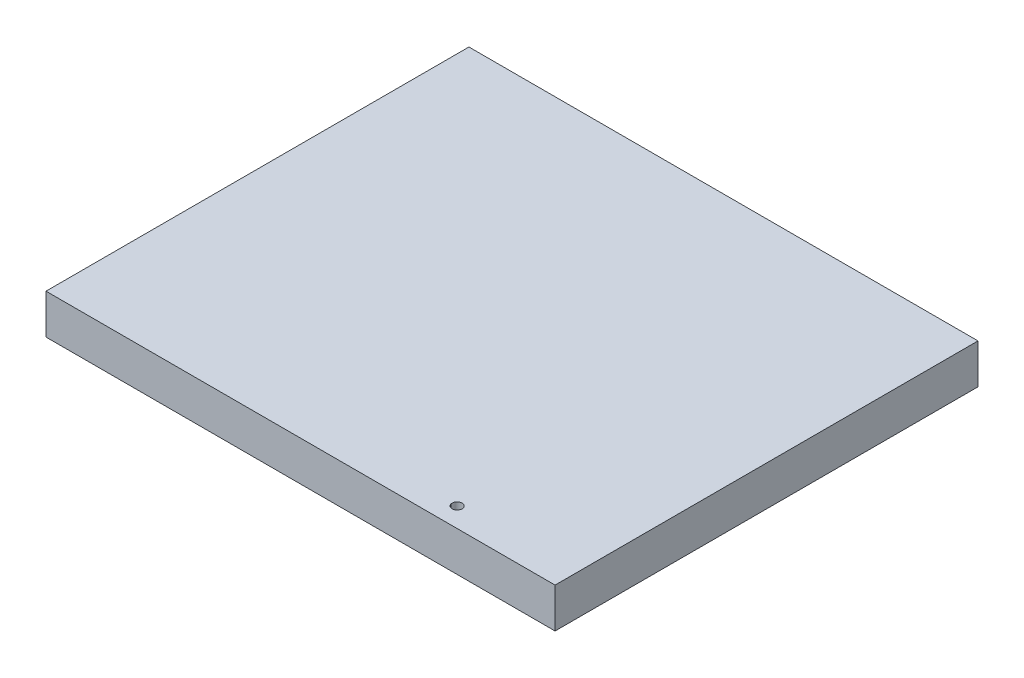
SolidWorks part; units mm, degrees
ref_plane "Front Plane" through (0, 0, 0) normal (0, 0, 1) x (1, 0, 0)
ref_plane "Top Plane" through (0, 0, 0) normal (0, 1, 0) x (1, 0, 0)
ref_plane "Right Plane" through (0, 0, 0) normal (1, 0, 0) x (0, 0, -1)
sketch "Sketch2" plane through (0, 0, 0) normal (0, 1, 0) x (1, 0, 0)
  line L1 (-145.7944, 109.8836) -> (179.2056, 109.8836)
  line L2 (-145.7944, 109.8836) -> (-145.7944, -160.1164)
  line L3 (-145.7944, -160.1164) -> (179.2056, -160.1164)
  line L4 (179.2056, 109.8836) -> (179.2056, -160.1164)
extrude "Boss-Extrude1" add sketch "Sketch2" along normal blind 25.4
sketch "Sketch5" plane through (0, 25.4, 0) normal (0, 1, 0) x (1, 0, 0)
  circle A0 centre (104.2056, -147.6164) radius 3.2
extrude "Cut-Extrude2" cut sketch "Sketch5" against normal blind 25.4
